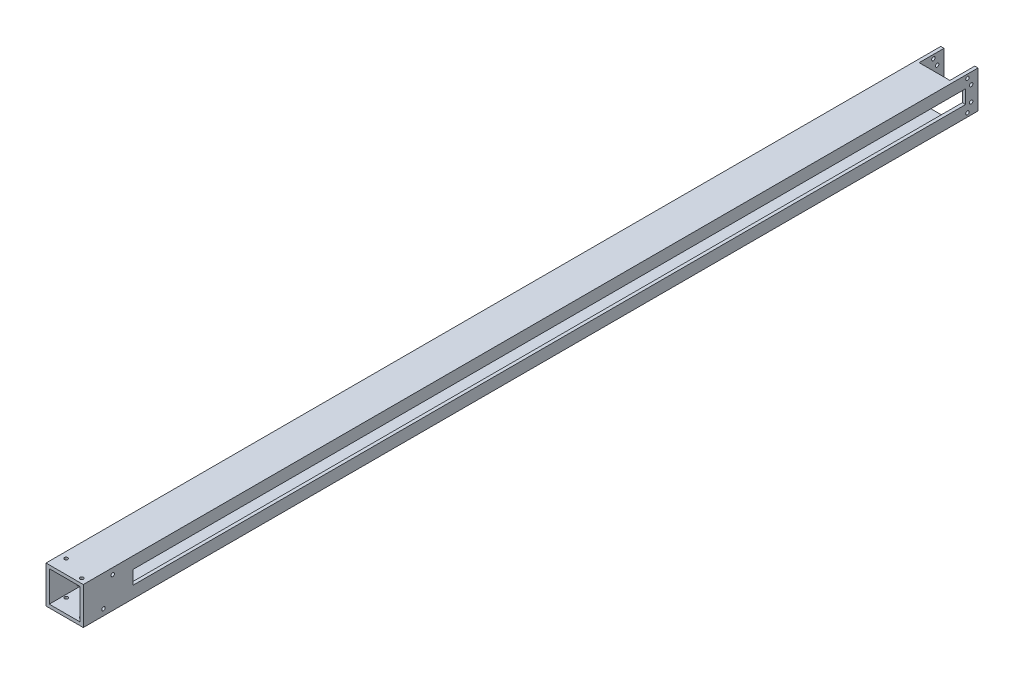
SolidWorks part; units mm, degrees
ref_plane "Front Plane" through (0, 0, 0) normal (1, 0, 0) x (0, 1, 0)
ref_plane "Top Plane" through (0, 0, 0) normal (0, 0, 1) x (0, 1, 0)
ref_plane "Right Plane" through (0, 0, 0) normal (0, 1, 0) x (-1, 0, 0)
sketch "Sketch1" plane through (0, 0, 0) normal (0, 0, 1) x (0, 1, 0)
  line L0 (19.05, -19.05) -> (19.05, 19.05)
  line L1 (19.05, -19.05) -> (-19.05, -19.05)
  line L2 (19.05, -19.05) -> (19.05, 19.05)
  line L3 (19.05, 19.05) -> (-19.05, 19.05)
  line L4 (-19.05, -19.05) -> (-19.05, 19.05)
  line L5 (19.05, -19.05) -> (-19.05, 19.05) construction
  line L6 (19.05, 19.05) -> (-19.05, -19.05) construction
  line L7 (19.05, 19.05) -> (-19.05, 19.05)
  line L8 (-19.05, -19.05) -> (-19.05, 19.05)
  line L9 (19.05, -19.05) -> (-19.05, -19.05)
  line L10 (15.7163, 15.7163) -> (-15.7162, 15.7163)
  line L11 (-15.7162, -15.7163) -> (-15.7162, 15.7163)
  line L12 (15.7163, -15.7162) -> (-15.7162, -15.7163)
  line L13 (15.7163, -15.7162) -> (15.7163, 15.7163)
  line L14 (-6.985, -15.7162) -> (-6.985, -19.05)
  line L15 (6.985, -15.7163) -> (6.985, -19.05)
  line L16 (-15.7162, -15.7163) -> (-6.985, -15.7162)
  line L17 (-6.985, -17.3831) -> (-19.05, -17.3831) construction
  line L18 (6.985, -17.3831) -> (19.05, -17.3831) construction
  point P0 (0, 0)
  dimension "D1" = 38.1
  dimension "D4" = 13.97
  dimension "D3" = 31.4325
  dimension "D2" = 0
extrude "Boss-Extrude1" add sketch "Sketch1" along normal blind 914.4 contours L4 L1 L0 L3 L13 L12 L11 L10
sketch "Sketch6" plane through (0, 0, 0) normal (0, 0, 1) x (0, 1, 0)
  line L1 (26.9875, -26.9875) -> (-26.9875, -26.9875) construction
  line L2 (26.9875, -26.9875) -> (26.9875, 26.9875) construction
  line L3 (26.9875, 26.9875) -> (-26.9875, 26.9875) construction
  line L4 (-26.9875, -26.9875) -> (-26.9875, 26.9875) construction
  line L5 (26.9875, -26.9875) -> (-26.9875, 26.9875) construction
  line L6 (26.9875, 26.9875) -> (-26.9875, -26.9875) construction
  line L11 (-26.9875, 25.8156) -> (-16.9875, 25.8156)
  line L12 (-26.9875, 25.8156) -> (-26.9875, 21.8156)
  line L13 (-26.9875, 21.8156) -> (-16.9875, 21.8156)
  line L14 (-16.9875, 25.8156) -> (-16.9875, 21.8156)
  line L15 (-23.4875, 25.8156) -> (-20.4875, 25.8156)
  line L16 (-23.4875, 25.8156) -> (-23.4875, -2.5726)
  line L17 (-23.4875, -2.5726) -> (-20.4875, -2.5726)
  line L18 (-20.4875, 25.8156) -> (-20.4875, -2.5726)
  point P0 (0, 0)
  point P14 (-21.9875, 25.8156)
  point P15 (-21.9875, 25.8156)
  dimension "D1" = 53.975
  dimension "D2" = 4
  dimension "D3" = 10
  dimension "D4" = 3
sketch "Sketch7" plane through (0, 0, 0) normal (0, 1, 0) x (-1, 0, 0)
  line L0 (-19.05, 914.4) -> (19.05, 914.4) construction
  line L1 (-12.7, 911.3875) -> (-12.7, 907.8875) construction
  line L2 (12.7, 900.1125) -> (-12.7, 900.1125) construction
  line L3 (12.7, 900.1125) -> (12.7, 909.6375) construction
  line L4 (12.7, 909.6375) -> (-12.7, 909.6375) construction
  line L5 (-12.7, 900.1125) -> (-12.7, 909.6375) construction
  line L6 (12.7, 900.1125) -> (-12.7, 909.6375) construction
  line L7 (12.7, 909.6375) -> (-12.7, 900.1125) construction
  line L8 (-19.05, 914.4) -> (-19.05, 0) construction
  circle A0 centre (-12.7, 909.6375) radius 1.75
  circle A1 centre (12.7, 900.1125) radius 1.75
  point P0 (0, 914.4)
  point P2 (0, 904.875)
  dimension "D2" = 3.5
  dimension "D1" = 9.525
  dimension "D3" = 4.7625
  dimension "D4" = 6.35
extrude "Cut-Extrude2" cut sketch "Sketch7" along normal blind 70.104 and the other way blind 58.42
sketch "Sketch8" plane through (0, 19.05, 0) normal (0, 1, 0) x (-1, 0, 0)
  line L0 (-19.05, 0) -> (19.05, 0) construction
  line L1 (15.7163, -25.4) -> (-15.7162, -25.4)
  line L2 (15.7163, -25.4) -> (15.7163, 25.4)
  line L3 (15.7163, 25.4) -> (-15.7162, 25.4)
  line L4 (-15.7162, -25.4) -> (-15.7162, 25.4)
  line L5 (15.7163, -25.4) -> (-15.7162, 25.4) construction
  line L6 (15.7163, 25.4) -> (-15.7162, -25.4) construction
  point P0 (0, 0)
  dimension "1.25" = 31.4325
  dimension "D2" = 25.4
extrude "Cut-Extrude3" cut sketch "Sketch8" against normal blind 71.882
sketch "Sketch10" plane through (19.05, 0, 0) normal (1, 0, 0) x (0, 1, 0)
  line L0 (-12.7, 895.5125) -> (-12.7, 892.0125) construction
  line L1 (12.7, 884.2375) -> (-12.7, 884.2375) construction
  line L2 (12.7, 884.2375) -> (12.7, 893.7625) construction
  line L3 (12.7, 893.7625) -> (-12.7, 893.7625) construction
  line L4 (-12.7, 884.2375) -> (-12.7, 893.7625) construction
  line L5 (12.7, 884.2375) -> (-12.7, 893.7625) construction
  line L6 (12.7, 893.7625) -> (-12.7, 884.2375) construction
  line L8 (15.7163, 914.4) -> (-15.7162, 914.4) construction
  line L9 (-15.7162, 914.4) -> (-15.7163, 25.4) construction
  line L10 (-15.7162, 914.4) -> (-15.7163, 25.4) construction
  circle A0 centre (-12.7, 893.7625) radius 1.75
  circle A1 centre (12.7, 884.2375) radius 1.75
  point P0 (0, 889)
  point P1 (0, 889)
  point P13 (0, 914.4)
  dimension "D2" = 3.5
  dimension "D1" = 9.525
  dimension "D3" = 25.4
  dimension "D4" = 25.4
extrude "Cut-Extrude5" cut sketch "Sketch10" against normal blind 12.7
ref_axis "Axis1" through (0, 0, 746.76) along (0, 0, -1)
sketch "Sketch11" plane through (19.05, 0, 0) normal (1, 0, 0) x (0, 1, 0)
  line L0 (6.985, 914.4) -> (6.985, 0) construction
  line L1 (-6.985, 0) -> (6.985, 0)
  line L2 (-6.985, 0) -> (-6.985, 12.7)
  line L3 (-6.985, 12.7) -> (6.985, 12.7)
  line L4 (6.985, 0) -> (6.985, 12.7)
  dimension "D1" = 12.7
extrude "Boss-Extrude2" add sketch "Sketch11" against normal up to surface (3.3338 mm away) up to face at (15.7163, -10.95, 893.7625)
sketch "Sketch9" plane through (19.05, 0, 0) normal (1, 0, 0) x (0, 1, 0)
  line L0 (19.05, 0) -> (-19.05, 0) construction
  line L1 (19.05, 0) -> (-19.05, 0) construction
  line L2 (19.05, 0) -> (-19.05, 0) construction
  line L3 (19.05, 0) -> (-19.05, 0) construction
  line L4 (15.7163, 25.4) -> (19.05, 25.4) construction
  line L6 (15.7163, 25.4) -> (19.05, 25.4) construction
  line L10 (0, 0) -> (0, 6.35) construction
  circle A0 centre (-15.24, 10.795) radius 1.75
  circle A2 centre (15.24, 10.795) radius 1.75
  circle A3 centre (15.24, 10.795) radius 10.541 construction
  circle A5 centre (7.62, 6.985) radius 1.75
  circle A6 centre (-7.62, 6.985) radius 1.75
  point P12 (4.699, 10.795)
  point P15 (-15.24, 10.795)
  dimension "D2" = 3.5
  dimension "D3" = 6.35
  dimension "D5" = 21.082
  dimension "D7" = 7.62
  dimension "D1" = 0
  dimension "D4" = 15.24
  dimension "D6" = 10.795
  dimension "D8" = 3.81
extrude "Cut-Extrude4" cut sketch "Sketch9" against normal blind 68.326
pattern_circular "CirPattern1" count 3 every 180 about axis through (0, 0, 746.76) along (0, 0, -1) of "Cut-Extrude5"
sketch "Sketch12" plane through (19.05, 0, 0) normal (1, 0, 0) x (0, 1, 0)
  line L0 (19.05, 914.4) -> (19.05, 0) construction
  line L1 (-19.05, 914.4) -> (19.05, 914.4)
  line L2 (-19.05, 914.4) -> (-19.05, 863.6)
  line L3 (-19.05, 863.6) -> (19.05, 863.6)
  line L4 (19.05, 914.4) -> (19.05, 863.6)
  circle A0 centre (12.7, 884.2375) radius 1.75 construction
  circle A1 centre (-12.7, 893.7625) radius 1.75 construction
  circle A2 centre (12.7, 884.2375) radius 1.75
  circle A3 centre (-12.7, 893.7625) radius 1.75
  dimension "D1" = 50.8
extrude "Boss-Extrude3" add sketch "Sketch12" against normal up to surface (3.3338 mm away) up to face at (15.7163, -13.49, 10.795)
